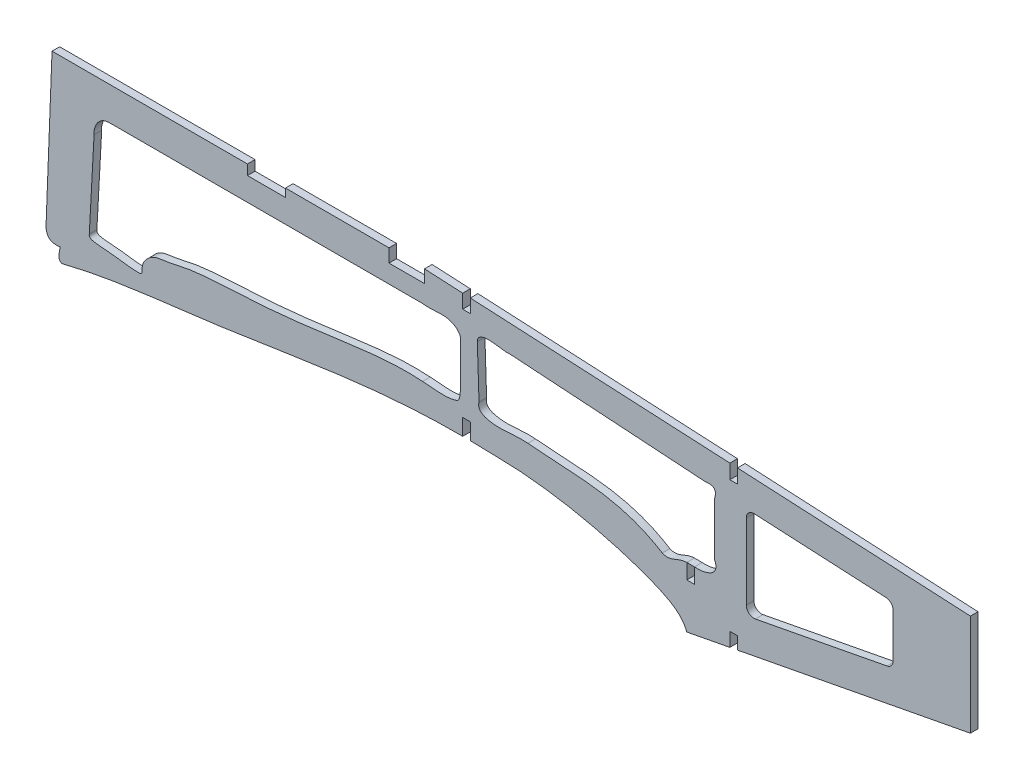
SolidWorks part; units mm, degrees
ref_plane "Front Plane" through (0, 0, 0) normal (0, 0, 1) x (1, 0, 0)
ref_plane "Top Plane" through (0, 0, 0) normal (0, 1, 0) x (1, 0, 0)
ref_plane "Right Plane" through (0, 0, 0) normal (1, 0, 0) x (0, 0, -1)
sketch "Sketch1" plane through (0, 0, 0) normal (0, 0, 1) x (1, 0, 0)
  line L0 (0, 0) -> (110, 0) construction
  line L1 (110, 0) -> (110, 21) construction
  line L2 (0, 0) -> (110, 21)
  line L3 (23.5, 17.3139) -> (20, 16.6457)
  line L4 (0, 0) -> (20, 0)
  line L5 (20, 0) -> (20, 67.15) construction
  line L6 (0, 0) -> (0, 67.15) construction
  line L7 (0, 67.15) -> (110, 67.15) construction
  line L8 (110, 61.55) -> (110, 67.15)
  line L9 (0, 67.15) -> (110, 61.55)
  line L10 (23.5, 53.9381) -> (81.5, 50.9854)
  line L11 (81.5, 50.9854) -> (81.5, 28.3866)
  line L12 (23.5, 53.9381) -> (23.5, 17.3139)
  line L13 (23.5, 17.3139) -> (81.5, 28.3866)
  line L14 (110, 21) -> (110, 61.55) construction
  line L15 (112, 61.4482) -> (112, 21.3818)
  line L16 (110, 61.55) -> (112, 61.4482)
  line L17 (110, 21) -> (112, 21.3818)
  line L18 (10.9, 67.15) -> (10.9, 0)
  line L19 (0, 67.15) -> (-82.3902, 71.3444)
  line L20 (0, 0) -> (-182.0672, -34.7583)
  line L21 (-86.7, -36.2944) -> (-86.7, -57.7944)
  line L22 (-93.05, 89.1409) -> (-93.05, -40.6456)
  line L23 (-70.5516, 60.184) -> (7.4462, 55.0566)
  line L24 (-89.4413, 54.3923) -> (-89.4413, 37.6042)
  line L25 (-65.3332, 22.0194) -> (-42.2468, 20.2821) construction
  line L26 (-42.2468, 20.2821) -> (-21.4079, 14.5616) construction
  line L27 (-21.4079, 14.5616) -> (-8.5368, 8.8411) construction
  line L28 (-8.5368, 8.8411) -> (-2.8162, 7.0023) construction
  line L29 (-2.8162, 7.0023) -> (0, 0) construction
  line L30 (-235.9653, 18.0968) -> (-234.0715, 53.1142)
  line L31 (-238.05, 59.4719) -> (-238.05, 21) construction
  line L32 (-921.7383, -124.7627) -> (144.2786, -161.9889) construction
  line L33 (28.3555, -1.516) -> (-255.9244, -1.516)
  line L34 (-226.3459, 60.184) -> (-104.3294, 60.184)
  line L35 (-82.0567, 37.6042) -> (-82.7237, 57.9466)
  line L36 (-82.3902, 71.3444) -> (-103.6, 72.4242)
  line L37 (-103.6, 72.4242) -> (-103.6, 67.1242)
  line L38 (-103.6, 67.1242) -> (-117.6, 67.1242)
  line L39 (-117.6, 67.1242) -> (-117.6, 72.6011)
  line L40 (-117.6, 72.6011) -> (-158.5, 72.6011)
  line L41 (-158.5, 72.6011) -> (-158.5, 68.6011)
  line L42 (-158.5, 68.6011) -> (-173.5, 69.3647)
  line L43 (-173.5, 69.3647) -> (-173.5, 73.3311)
  line L44 (-173.5, 73.3311) -> (-250.6778, 73.3311)
  line L45 (-250.6778, 73.3311) -> (-251.1351, 64.35)
  line L46 (-251.1351, 64.35) -> (-249.1426, 59.4719)
  line L47 (-249.1426, 59.4719) -> (-253.0614, 11.9612)
  spline_without_curve S0
  spline S1 degree 3 poles (-62.7428, 33.1676) (-50.008, 31.9642) (-31.0962, 32.5015) (-14.1751, 24.9914) (-9.6822, 22.192) knots 0 0 0 0 0.709755 1 1 1 1
  spline S2 degree 3 poles (-9.6822, 22.192) (-6.8917, 20.9668) (-4.0654, 23.2801) (1.077, 24.0309) (6.7349, 23.1276) (13.0796, 25.9871) (10.9, 30.3114) knots 0 0 0 0 0.304362 0.391412 0.603771 1 1 1 1
  spline S3 degree 3 poles (-65.3332, 22.0194) (-77.4805, 22.6509) (-98.8967, 23.1079) (-139.7694, 19.7032) (-187.7649, 10.9991) (-227.3069, 7.5749) (-246.6861, 2.6333) knots 0 0 0 0 0.199692 0.351003 0.672194 1 1 1 1
  spline S4 degree 3 poles (-62.7428, 33.1676) (-67.9368, 33.6388) (-74.1452, 31.6619) (-82.8627, 34.4448) (-82.0567, 37.6042) knots 0 0 0 0 0.65977 1 1 1 1
  spline S5 degree 3 poles (-104.3294, 60.184) (-100.5301, 59.5513) (-93.8007, 61.9485) (-88.7866, 56.5953) (-89.4413, 54.3923) knots 0 0 0 0 0.661964 1 1 1 1
  spline S6 degree 3 poles (-104.3294, 33.547) (-100.6826, 33.3941) (-97.3824, 32.6768) (-91.1309, 33.381) (-89.6784, 34.473) (-89.4413, 37.6042) knots 0 0 0 0 0.555991 0.846219 1 1 1 1
  spline S7 degree 3 poles (-104.3294, 33.547) (-116.4931, 34.3961) (-139.9294, 30.8214) (-169.9623, 27.1478) (-193.8607, 26.9431) (-204.0402, 24.0023) (-211.1217, 23.2564) (-214.8026, 19.376) (-215.2918, 15.9456) (-214.9447, 14.6164) (-218.1891, 14.6988) (-221.7312, 14.9192) (-230.6867, 16.3937) (-236.4685, 15.9971) (-235.9653, 18.0968) knots 0 0 0 0 0.241116 0.431915 0.666521 0.747659 0.783153 0.799752 0.821748 0.858269 0.866885 0.907914 0.932706 1 1 1 1
  spline S8 degree 3 poles (-82.7237, 57.9466) (-82.8248, 63.2577) (-71.0235, 59.3637) (-70.5516, 60.184) knots 0 0 0 0 1 1 1 1
  spline S9 degree 2 poles (7.4462, 55.0566) (12.5645, 55.8042) (10.9, 50.909) knots 0 0 0 1 1 1
  spline S10 degree 3 poles (-234.0715, 53.1142) (-234.3359, 55.4474) (-232.0516, 60.1047) (-228.0459, 60.2249) (-226.3459, 60.184) knots 0 0 0 0 0.618254 1 1 1 1
  spline S11 degree 2 poles (-253.0614, 11.9612) (-252.6953, 7.068) (-247.464, 8.0018) knots 0 0 0 1 1 1
  spline S12 degree 3 poles (-246.6861, 2.6333) (-248.9283, 3.1544) (-247.5659, 6.6016) (-247.464, 8.0018) knots 0 0 0 0 1 1 1 1
  point P55 (-93.05, 46.4253)
  dimension "D1" = 110
  dimension "D2" = 21
  dimension "D3" = 12.6
  dimension "D4" = 20
  dimension "D5" = 67.15
  dimension "D6" = 5.6
  dimension "D7" = 110
  dimension "D8" = 12
  dimension "D9" = 3.5
  dimension "D10" = 58
  dimension "D11" = 2
  dimension "D12" = 12.6
  dimension "D13" = 97.6
  dimension "D14" = 6.35
  dimension "D15" = 14
  dimension "D16" = 145
  dimension "D17" = 15
  dimension "D18" = 40.9
  dimension "D19" = 10.55
  dimension "D20" = 5.3
  dimension "D21" = 4
sketch "Sketch2" plane through (0, 0, 0) normal (0, 0, 1) x (1, 0, 0)
  line L0 (0, 0) -> (110, 21) construction
  line L1 (0, 0) -> (110, 21)
  line L2 (112, 61.4482) -> (112, 21.3818) construction
  line L3 (112, 61.4482) -> (112, 21.3818)
  line L4 (-70.5516, 60.184) -> (7.4462, 55.0566) construction
  line L5 (110, 21) -> (112, 21.3818) construction
  line L6 (110, 21) -> (112, 21.3818)
  line L7 (110, 61.55) -> (112, 61.4482) construction
  line L8 (110, 61.55) -> (112, 61.4482)
  line L9 (0, 67.15) -> (110, 61.55) construction
  line L10 (0, 67.15) -> (110, 61.55)
  line L11 (0, 67.15) -> (-82.3902, 71.3444) construction
  line L12 (0, 67.15) -> (-82.3902, 71.3444)
  line L13 (-82.3902, 71.3444) -> (-103.6, 72.4242) construction
  line L14 (-82.3902, 71.3444) -> (-103.6, 72.4242)
  line L15 (-103.6, 72.4242) -> (-103.6, 67.3782)
  line L16 (-103.6, 67.3782) -> (-117.6, 67.3782)
  line L17 (-117.6, 67.3782) -> (-117.6, 72.6011)
  line L18 (-117.6, 72.6011) -> (-158.5, 72.6011)
  line L19 (-158.5, 72.6011) -> (-158.5, 69.3647)
  line L20 (-158.5, 69.3647) -> (-173.5, 69.3647)
  line L21 (-173.5, 69.3647) -> (-173.5, 73.3311)
  line L22 (-173.5, 73.3311) -> (-250.6778, 73.3311) construction
  line L23 (-173.5, 73.3311) -> (-250.6778, 73.3311)
  line L24 (-250.6778, 73.3311) -> (-253.0614, 11.9612)
  line L25 (-89.4413, 54.3923) -> (-89.4413, 37.6042) construction
  line L26 (-226.3459, 60.184) -> (-104.3294, 60.184) construction
  line L27 (-235.9653, 18.0968) -> (-234.0715, 53.1142) construction
  line L28 (-89.4413, 54.3923) -> (-89.4413, 37.6042)
  line L29 (-226.3459, 60.184) -> (-104.3294, 60.184)
  line L30 (-235.9653, 18.0968) -> (-234.0715, 53.1142)
  line L31 (-82.0567, 37.6042) -> (-82.7237, 57.9466) construction
  line L32 (-70.5516, 60.184) -> (7.4462, 55.0566)
  line L33 (-82.0567, 37.6042) -> (-82.7237, 57.9466)
  line L34 (10.9, 50.909) -> (10.9, 30.3114)
  line L35 (81.5, 50.9854) -> (81.5, 28.3866) construction
  line L36 (23.5, 17.3139) -> (81.5, 28.3866) construction
  line L37 (23.5, 53.9381) -> (81.5, 50.9854) construction
  line L38 (23.5, 53.9381) -> (23.5, 17.3139) construction
  line L39 (81.5, 48.1342) -> (81.5, 30.8681)
  line L40 (27.0626, 17.994) -> (79.0626, 27.9213)
  line L41 (26.6525, 53.7776) -> (78.6525, 51.1303)
  line L42 (23.5, 50.7815) -> (23.5, 20.9408)
  line L43 (-158.5, 72.6011) -> (-158.5, 68.6011) construction
  arc A0 (26.6525, 53.7776) -> (23.5, 50.7815) centre (26.5, 50.7815) ccw
  arc A1 (27.0626, 17.994) -> (23.5, 20.9408) centre (26.5, 20.9408) cw
  arc A2 (81.5, 30.8681) -> (79.0626, 27.9213) centre (78.5, 30.8681) cw
  arc A3 (81.5, 48.1342) -> (78.6525, 51.1303) centre (78.5, 48.1342) ccw
  parabola Q0 (-253.0614, 11.9612) -> (-247.464, 8.0018) focus (-250.6889, 9.8561) apex (-251.6748, 8.6753) construction
  parabola Q1 (-253.0614, 11.9612) -> (-247.464, 8.0018) focus (-250.6889, 9.8561) apex (-251.6748, 8.6753)
  parabola Q2 (7.4462, 55.0566) -> (10.9, 50.909) focus (10.2347, 53.865) apex (10.8693, 54.3929) construction
  parabola Q3 (7.4462, 55.0566) -> (10.9, 50.909) focus (10.2347, 53.865) apex (10.8693, 54.3929)
  spline S0 degree 3 poles (495.0711, 673.2984) (-978.3405, -729.0238) (461.9208, 762.2994) (-928.2816, -724.421) knots -4.620219 -4.620219 -4.620219 -4.620219 5.948907 5.948907 5.948907 5.948907 only from (-246.6861, 2.6333) to (-247.464, 8.0018) construction
  spline S1 degree 3 poles (-246.6861, 2.6333) (-248.9283, 3.1544) (-247.5659, 6.6016) (-247.464, 8.0018) knots 0 0 0 0 1 1 1 1
  spline S2 degree 3 poles (250.8163, 970.7277) (298.3945, -152.3549) (85.6556, 38.4812) (-139.7694, 19.7032) (-292.96, -8.0781) (-445.5874, 15.6129) (-391.6414, -986.8008) knots -3.035159 -3.035159 -3.035159 -3.035159 0.199692 0.351003 0.672194 2.75409 2.75409 2.75409 2.75409 only from (-65.3332, 22.0194) to (-246.6861, 2.6333) construction
  spline S3 degree 3 poles (-65.3332, 22.0194) (-77.4805, 22.6509) (-98.8967, 23.1079) (-139.7694, 19.7032) (-187.7649, 10.9991) (-227.3069, 7.5749) (-246.6861, 2.6333) knots 0 0 0 0 0.199692 0.351003 0.672194 1 1 1 1
  spline S4 degree 5 poles (934.6646, 22.8625) (-1053.1807, -522.9285) (274.7656, 934.5247) (97.2906, -1026.2662) (-186.4643, 1019.1097) (177.8864, -984.0058) knots -2.123408 -2.123408 -2.123408 -2.123408 -2.123408 -2.123408 2.541227 2.541227 2.541227 2.541227 2.541227 2.541227 only from (-65.3332, 22.0194) to (0, 0) construction
  spline S5 degree 5 poles (-65.3332, 22.0194) (-42.2468, 20.2821) (-21.4079, 14.5616) (-8.5368, 8.8411) (-2.8162, 7.0023) (0, 0) knots 0 0 0 0 0 0 1 1 1 1 1 1
  spline S6 degree 3 poles (-1058.6269, -265.3049) (-91.5706, 64.6884) (-120.478, 30.0751) (-85.1958, 34.0496) (-89.5168, 42.7055) (-140.6717, 1036.1992) knots -3.694414 -3.694414 -3.694414 -3.694414 0.555991 0.846219 1.949398 1.949398 1.949398 1.949398 only from (-104.3294, 33.547) to (-89.4413, 37.6042) construction
  spline S7 degree 3 poles (-416.8222, -916.3639) (78.8732, 70.4595) (-76.3983, 38.5925) (-169.9623, 27.1478) (-193.8607, 26.9431) (-204.0402, 24.0023) (-211.1217, 23.2564) (-214.8026, 19.376) (-215.2918, 15.9456) (-214.9447, 14.6164) (-218.1891, 14.6988) (-221.7312, 14.9192) (-252.4654, 19.9795) (-272.0115, -4.2986) (601.3635, 564.5091) knots -1.409949 -1.409949 -1.409949 -1.409949 0.241116 0.431915 0.666521 0.747659 0.783153 0.799752 0.821748 0.858269 0.866885 0.907914 0.932706 1.323719 1.323719 1.323719 1.323719 only from (-104.3294, 33.547) to (-235.9653, 18.0968) construction
  spline S8 degree 3 poles (361.1726, 856.6546) (-222.0495, -68.9915) (-273.2082, 172.2443) (-153.5088, -36.8752) (-232.7053, 1060.1591) knots -4.31027 -4.31027 -4.31027 -4.31027 0.618254 5.652754 5.652754 5.652754 5.652754 only from (-234.0715, 53.1142) to (-226.3459, 60.184) construction
  spline S9 degree 3 poles (-104.3294, 33.547) (-100.6826, 33.3941) (-97.3824, 32.6768) (-91.1309, 33.381) (-89.6784, 34.473) (-89.4413, 37.6042) knots 0 0 0 0 0.555991 0.846219 1 1 1 1
  spline S10 degree 3 poles (-104.3294, 33.547) (-116.4931, 34.3961) (-139.9294, 30.8214) (-169.9623, 27.1478) (-193.8607, 26.9431) (-204.0402, 24.0023) (-211.1217, 23.2564) (-214.8026, 19.376) (-215.2918, 15.9456) (-214.9447, 14.6164) (-218.1891, 14.6988) (-221.7312, 14.9192) (-230.6867, 16.3937) (-236.4685, 15.9971) (-235.9653, 18.0968) knots 0 0 0 0 0.241116 0.431915 0.666521 0.747659 0.783153 0.799752 0.821748 0.858269 0.866885 0.907914 0.932706 1 1 1 1
  spline S11 degree 3 poles (-234.0715, 53.1142) (-234.3359, 55.4474) (-232.0516, 60.1047) (-228.0459, 60.2249) (-226.3459, 60.184) knots 0 0 0 0 0.618254 1 1 1 1
  spline S12 degree 3 poles (87.8273, 1041.5446) (-167.2404, -48.9181) (-82.2161, 146.8164) (-74.8317, -8.2566) (-1088.0017, 107.563) knots -3.444495 -3.444495 -3.444495 -3.444495 0.661964 3.28329 3.28329 3.28329 3.28329 only from (-104.3294, 60.184) to (-89.4413, 54.3923) construction
  spline S13 degree 3 poles (-104.3294, 60.184) (-100.5301, 59.5513) (-93.8007, 61.9485) (-88.7866, 56.5953) (-89.4413, 54.3923) knots 0 0 0 0 0.661964 1 1 1 1
  spline S14 degree 3 poles (-256.3001, 991.3018) (-21.7618, -31.8195) (-18.2551, 21.2081) (1.077, 24.0309) (20.7945, 20.8829) (60.3759, 71.677) (-951.0315, 303.5414) knots -1.666051 -1.666051 -1.666051 -1.666051 0.304362 0.391412 0.603771 2.728629 2.728629 2.728629 2.728629 only from (-9.6822, 22.192) to (10.9, 30.3114) construction
  spline S15 degree 3 poles (44.9632, 1027.3482) (-220.6038, -86.1213) (20.5956, 195.5033) (95.6984, -194.3204) (-946.9004, -326.545) knots -3.764454 -3.764454 -3.764454 -3.764454 0.709755 5.369919 5.369919 5.369919 5.369919 only from (-62.7428, 33.1676) to (-9.6822, 22.192) construction
  spline S16 degree 3 poles (498.3977, -794.5478) (-56.0926, 111.8171) (-37.0001, -12.7902) (-121.5126, 59.1481) (805.2199, 498.8342) knots -3.658664 -3.658664 -3.658664 -3.658664 0.65977 2.767333 2.767333 2.767333 2.767333 only from (-62.7428, 33.1676) to (-82.0567, 37.6042) construction
  spline S17 degree 3 poles (730.6506, -523.7856) (-984.6325, 618.857) (854.3716, -462.9713) (-947.0939, 541.4638) knots -2.829974 -2.829974 -2.829974 -2.829974 3.935684 3.935684 3.935684 3.935684 only from (-82.7237, 57.9466) to (-70.5516, 60.184) construction
  spline S18 degree 3 poles (-9.6822, 22.192) (-6.8917, 20.9668) (-4.0654, 23.2801) (1.077, 24.0309) (6.7349, 23.1276) (13.0796, 25.9871) (10.9, 30.3114) knots 0 0 0 0 0.304362 0.391412 0.603771 1 1 1 1
  spline S19 degree 3 poles (-62.7428, 33.1676) (-50.008, 31.9642) (-31.0962, 32.5015) (-14.1751, 24.9914) (-9.6822, 22.192) knots 0 0 0 0 0.709755 1 1 1 1
  spline S20 degree 3 poles (-62.7428, 33.1676) (-67.9368, 33.6388) (-74.1452, 31.6619) (-82.8627, 34.4448) (-82.0567, 37.6042) knots 0 0 0 0 0.65977 1 1 1 1
  spline S21 degree 3 poles (-82.7237, 57.9466) (-82.8248, 63.2577) (-71.0235, 59.3637) (-70.5516, 60.184) knots 0 0 0 0 1 1 1 1
  point P6 (-2.1894, 23.46)
  dimension "D1" = 3
  dimension "D2" = 3
  dimension "D3" = 14
extrude "Boss-Extrude1" add sketch "Sketch2" along normal blind 3
sketch "Sketch3" plane through (0, 0, 0) normal (0, 0, -1) x (-1, 0, 0)
  line L0 (-20, 0) -> (-20, 67.15) construction
  line L1 (-20, 0) -> (-20, 67.15)
  line L2 (0, 67.15) -> (-110, 61.55) construction
  line L3 (0, 23.8107) -> (0, -7.1001) construction
  line L4 (0, 67.15) -> (-110, 61.55)
  line L5 (-17, 66.2845) -> (-17, 60.5845)
  line L6 (-17, 60.5845) -> (-20, 60.5845)
  line L7 (-20, 60.5845) -> (-20, 66.1318)
  line L8 (-20, 66.1318) -> (-17, 66.2845)
  line L9 (0, 0) -> (-110, 21) construction
  line L10 (0, 0) -> (-110, 21)
  line L11 (-17, 8.7455) -> (-17, 3.2455)
  line L12 (-17, 8.7455) -> (-20, 8.7455)
  line L13 (-20, 8.7455) -> (-20, 3.7748)
  line L14 (-20, 3.7748) -> (-17, 3.2455)
  line L15 (85.5, 71.5027) -> (85.5, 66.1555)
  line L16 (88.5, 71.6555) -> (88.5, 66.1555)
  line L17 (82.3902, 71.3444) -> (103.6, 72.4242) construction
  line L18 (88.5, 66.1555) -> (85.5, 66.1555)
  line L19 (85.5, 71.5027) -> (88.5, 71.6555)
  line L20 (88.5, 29.1501) -> (88.5, 22.5501)
  line L21 (88.5, 29.1501) -> (85.5, 29.1501)
  line L22 (85.5, 22.6667) -> (88.5, 22.5501)
  line L23 (85.5, 29.1501) -> (85.5, 22.6667)
  line L24 (0, 23.8107) -> (0, 17.8107)
  line L25 (-3, 23.7752) -> (-3, 17.8107)
  line L26 (0, 17.8107) -> (-3, 17.8107)
  line L27 (-3, 23.7752) -> (0, 23.8107)
  spline S0 degree 3 poles (65.3332, 22.0194) (77.4805, 22.6509) (98.8967, 23.1079) (139.7694, 19.7032) (187.7649, 10.9991) (227.3069, 7.5749) (246.6861, 2.6333) knots 0 0 0 0 0.199692 0.351003 0.672194 1 1 1 1 construction
  spline S1 degree 3 poles (9.6822, 22.192) (6.8917, 20.9668) (4.0654, 23.2801) (-1.077, 24.0309) (-6.7349, 23.1276) (-13.0796, 25.9871) (-10.9, 30.3114) knots 0 0 0 0 0.304362 0.391412 0.603771 1 1 1 1 construction
  dimension "D1" = 3
  dimension "D2" = 5.7
  dimension "D3" = 5.5
  dimension "D4" = 105.5
  dimension "D5" = 3
  dimension "D6" = 5.5
  dimension "D7" = 6.6
  dimension "D8" = 20
  dimension "D9" = 6
  dimension "D10" = 3
extrude "Cut-Extrude1" cut sketch "Sketch3" against normal blind 10 contours L15 L18 L16 L19 | L22 L20 L21 L23 | L8 L5 L6 L7 | L27 L24 L26 L25 | L14 L11 L12 L13
